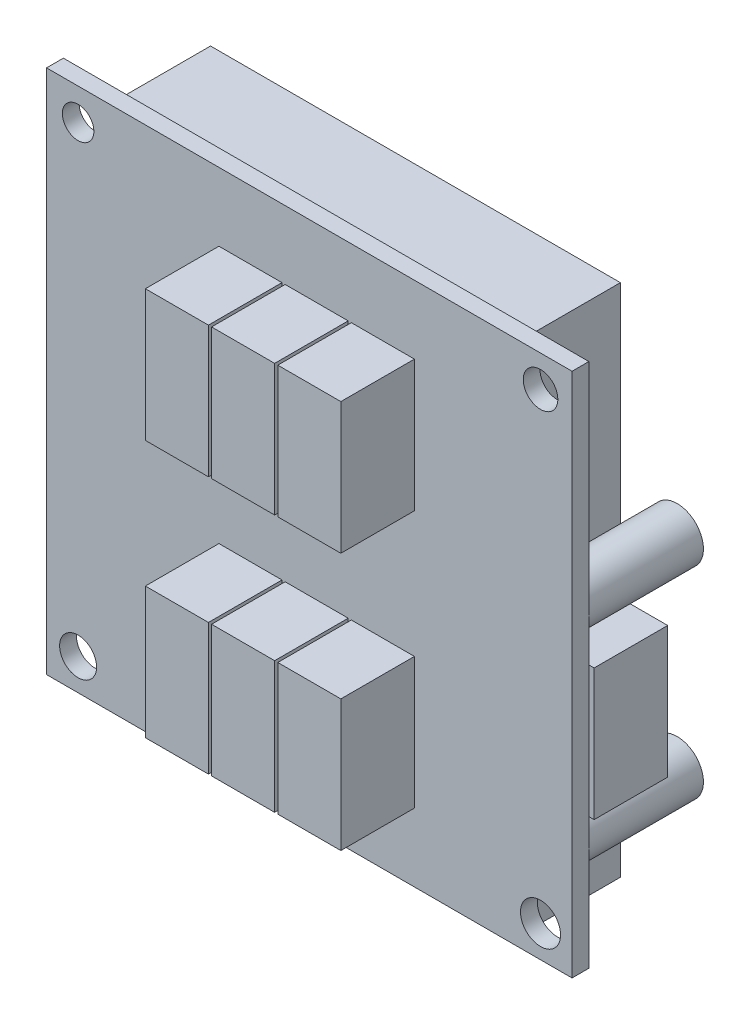
SolidWorks part; units mm, degrees
ref_plane "Front Plane" through (0, 0, 0) normal (0, 0, 1) x (1, 0, 0)
ref_plane "Top Plane" through (0, 0, 0) normal (0, 1, 0) x (1, 0, 0)
ref_plane "Right Plane" through (0, 0, 0) normal (1, 0, 0) x (0, 0, -1)
sketch "Sketch1" plane through (0, 0, 0) normal (0, 0, 1) x (1, 0, 0)
  line L0 (-25, 25) -> (25, 25)
  line L1 (25, 25) -> (25, -25)
  line L2 (25, -25) -> (-25, -25)
  line L3 (-25, -25) -> (-25, 25)
  line L4 (-25, 25) -> (25, -25)
  circle A0 centre (-22, 22) radius 1.5
  circle A1 centre (22, 22) radius 1.6469
  circle A2 centre (22, -22) radius 1.9082
  circle A3 centre (-22, -22) radius 1.7591
  dimension "D3" = 3
  dimension "D1" = 50
  dimension "D2" = 50
  dimension "D4" = 3
  dimension "D5" = 3
  dimension "D6" = 3
  dimension "D7" = 3
extrude "Extrude2" add sketch "Sketch1" along normal mid plane 1.6 contours L0 L4 L1 | L4 L3 L2
sketch "Sketch2" plane through (0, 0, 0.8) normal (0, 0, 1) x (1, 0, 0)
  line L0 (-25, 25) -> (25, 25) construction
  line L1 (10, 18.5) -> (4, 18.5)
  line L2 (10, 18.5) -> (10, 6)
  line L3 (10, 6) -> (4, 6)
  line L4 (4, 18.5) -> (4, 6)
  line L5 (10, -6) -> (4, -6)
  line L6 (10, -6) -> (10, -18.5)
  line L7 (10, -18.5) -> (4, -18.5)
  line L8 (4, -6) -> (4, -18.5)
  line L9 (3.7, 18.5) -> (-2.3, 18.5)
  line L10 (3.7, 18.5) -> (3.7, 6)
  line L11 (3.7, 6) -> (-2.3, 6)
  line L12 (-2.3, 18.5) -> (-2.3, 6)
  line L13 (3.7, -6) -> (-2.3, -6)
  line L14 (3.7, -6) -> (3.7, -18.5)
  line L15 (3.7, -18.5) -> (-2.3, -18.5)
  line L16 (-2.3, -6) -> (-2.3, -18.5)
  line L17 (-2.6, 18.5) -> (-8.6, 18.5)
  line L18 (-2.6, 18.5) -> (-2.6, 6)
  line L19 (-2.6, 6) -> (-8.6, 6)
  line L20 (-8.6, 18.5) -> (-8.6, 6)
  line L21 (-2.6, -6) -> (-8.6, -6)
  line L22 (-2.6, -6) -> (-2.6, -18.5)
  line L23 (-2.6, -18.5) -> (-8.6, -18.5)
  line L24 (-8.6, -6) -> (-8.6, -18.5)
  line L25 (25, -25) -> (-25, -25) construction
  line L26 (25, 25) -> (25, -25) construction
  dimension "D1" = 12.5
  dimension "D2" = 6
  dimension "D3" = 6.5
  dimension "D4" = 6.5
  dimension "D5" = 0.3
  dimension "D6" = 0.3
  dimension "D7" = 15
extrude "Extrude3" add sketch "Sketch2" along normal blind 7
sketch "Sketch3" plane through (0, 0, -0.8) normal (0, 0, -1) x (-1, 0, 0)
  line L0 (-25, 25) -> (-25, -25) construction
  line L1 (-25.5, -12.5) -> (-19.5, -12.5)
  line L2 (-25.5, -12.5) -> (-25.5, 0)
  line L3 (-25.5, 0) -> (-19.5, 0)
  line L4 (-19.5, -12.5) -> (-19.5, 0)
  line L5 (-25, -25) -> (25, -25) construction
  dimension "D1" = 0.5
  dimension "D2" = 6
  dimension "D3" = 12.5
  dimension "D4" = 12.5
extrude "Extrude4" add sketch "Sketch3" along normal blind 7
sketch "Sketch4" plane through (0, 0, -0.8) normal (0, 0, -1) x (-1, 0, 0)
  line L0 (-25, -25) -> (25, -25) construction
  line L1 (-19.5, -24.5) -> (19.5, -24.5)
  line L2 (-19.5, -24.5) -> (-19.5, -1.5)
  line L3 (-19.5, -1.5) -> (19.5, -1.5)
  line L4 (19.5, -24.5) -> (19.5, -1.5)
  line L5 (-19.5, 1.5) -> (19.5, 1.5)
  line L6 (-19.5, 1.5) -> (-19.5, 24.5)
  line L7 (-19.5, 24.5) -> (19.5, 24.5)
  line L8 (19.5, 1.5) -> (19.5, 24.5)
  line L9 (25, 25) -> (-25, 25) construction
  line L10 (25, -25) -> (25, 25) construction
  dimension "D1" = 23
  dimension "D2" = 39
  dimension "D3" = 0.5
  dimension "D4" = 0.5
  dimension "D5" = 5.5
extrude "Extrude5" add sketch "Sketch4" along normal blind 8.5
sketch "Sketch5" plane through (0, 0, -0.8) normal (0, 0, -1) x (-1, 0, 0)
  line L0 (25, -25) -> (25, 25) construction
  line L1 (-25, -12.5) -> (-25, -25) construction
  line L2 (-25, -25) -> (25, -25) construction
  circle A0 centre (22.4, -3) radius 2.5
  circle A1 centre (22.4, 3) radius 2.5
  circle A2 centre (-22.4, -15.2) radius 2.5
  circle A3 centre (-22.4, 4) radius 2.5
  dimension "D1" = 5
  dimension "D2" = 2.6
  dimension "D3" = 2.6
  dimension "D4" = 22
  dimension "D5" = 28
  dimension "D6" = 9.8
  dimension "D7" = 29
extrude "Extrude8" add sketch "Sketch5" along normal blind 11
